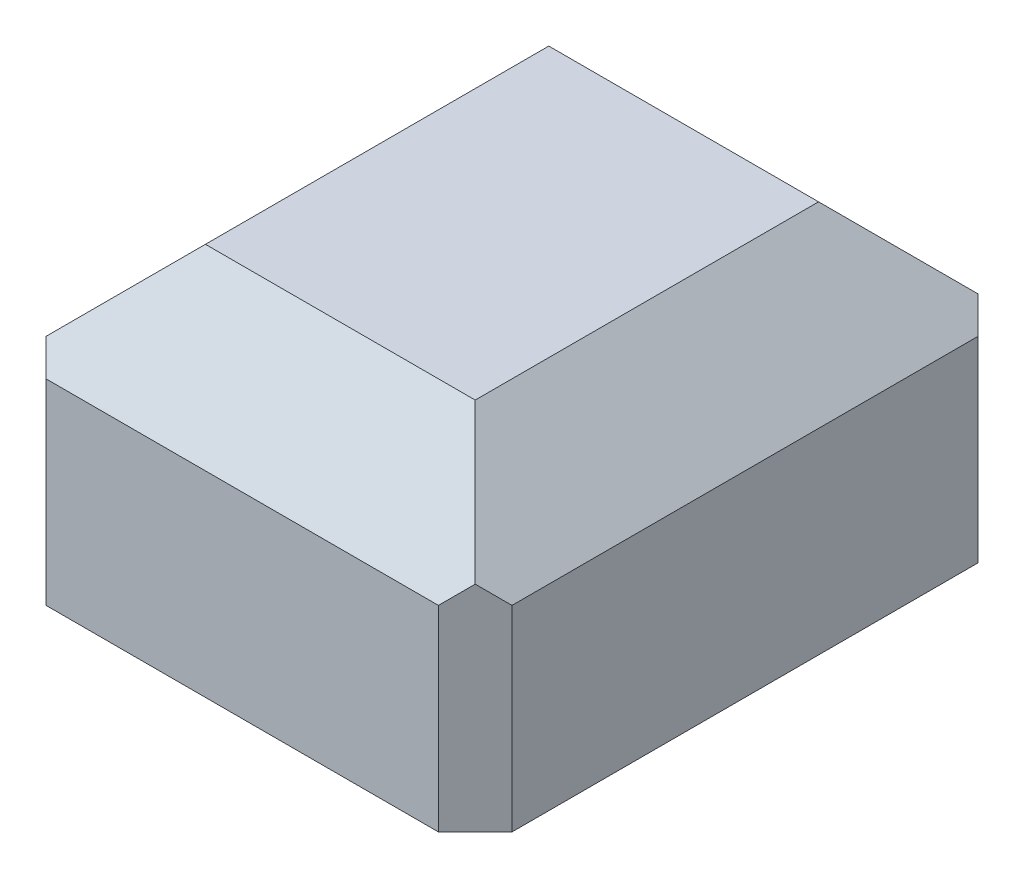
SolidWorks part; units mm, degrees
ref_plane "Front Plane" through (0, 0, 0) normal (0, 0, 1) x (1, 0, 0)
ref_plane "Top Plane" through (0, 0, 0) normal (0, 1, 0) x (1, 0, 0)
ref_plane "Right Plane" through (0, 0, 0) normal (1, 0, 0) x (0, 0, -1)
sketch "Sketch1" plane through (0, 0, 0) normal (0, 1, 0) x (1, 0, 0)
  line L1 (-95, -110) -> (95, -110)
  line L2 (-95, -110) -> (-95, 110)
  line L3 (-95, 110) -> (95, 110)
  line L4 (95, -110) -> (95, 110)
  line L5 (-95, -110) -> (95, 110) construction
  line L6 (-95, 110) -> (95, -110) construction
  point P0 (0, 0)
  dimension "D1" = 220
  dimension "D2" = 190
extrude "Boss-Extrude1" add sketch "Sketch1" along normal blind 120
chamfer "Chamfer1" distance 40 angle 45 4 edges at (0, 120, 110) (-95, 120, 0) (0, 120, -110) (95, 120, 0)
chamfer "Chamfer2" distance 15 angle 45 4 edges at (-95, 40, -110) (95, 40, -110) (95, 40, 110) (-95, 40, 110)
shell "Shell1" thickness 3
